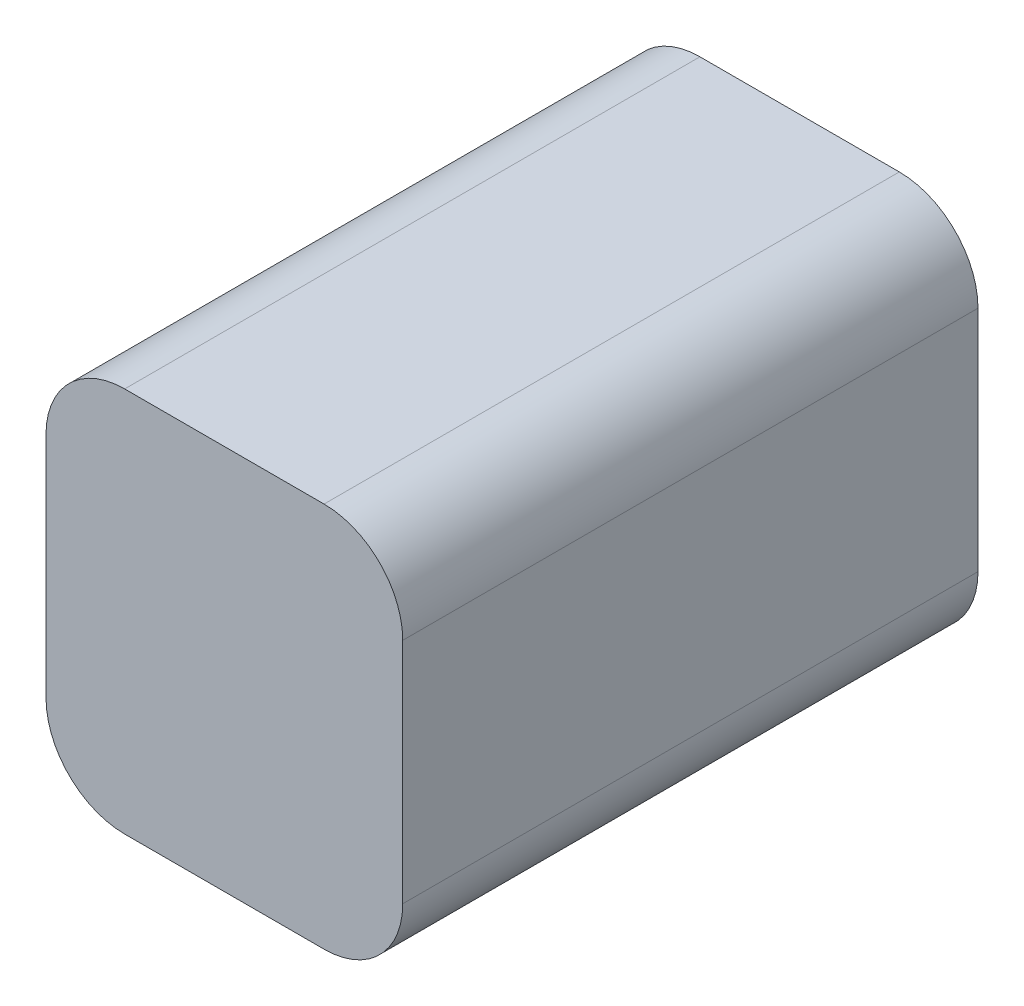
SolidWorks part; units mm, degrees
material "80% PETG"
ref_plane "Front Plane" through (0, 0, 0) normal (0, 0, 1) x (1, 0, 0)
ref_plane "Top Plane" through (0, 0, 0) normal (0, 1, 0) x (1, 0, 0)
ref_plane "Right Plane" through (0, 0, 0) normal (1, 0, 0) x (0, 0, -1)
sketch "Sketch1" plane through (0, 0, 0) normal (0, 0, 1) x (1, 0, 0)
  line L1 (22.78, 22.78) -> (22.78, -22.79)
  line L2 (22.78, -22.79) -> (-19.39, -22.79)
  line L3 (-19.39, -22.79) -> (-19.39, 22.78)
  line L5 (-19.39, 22.78) -> (22.78, 22.78)
  dimension "D1" = 45.57
  dimension "D2" = 42.17
extrude "Boss-Extrude1" add sketch "Sketch1" along normal blind 68
fillet "Fillet1" radius 9.3 4 edges at (-19.39, -22.79, 34) (-19.39, 22.78, 34) (22.78, 22.78, 34) (22.78, -22.79, 34)
